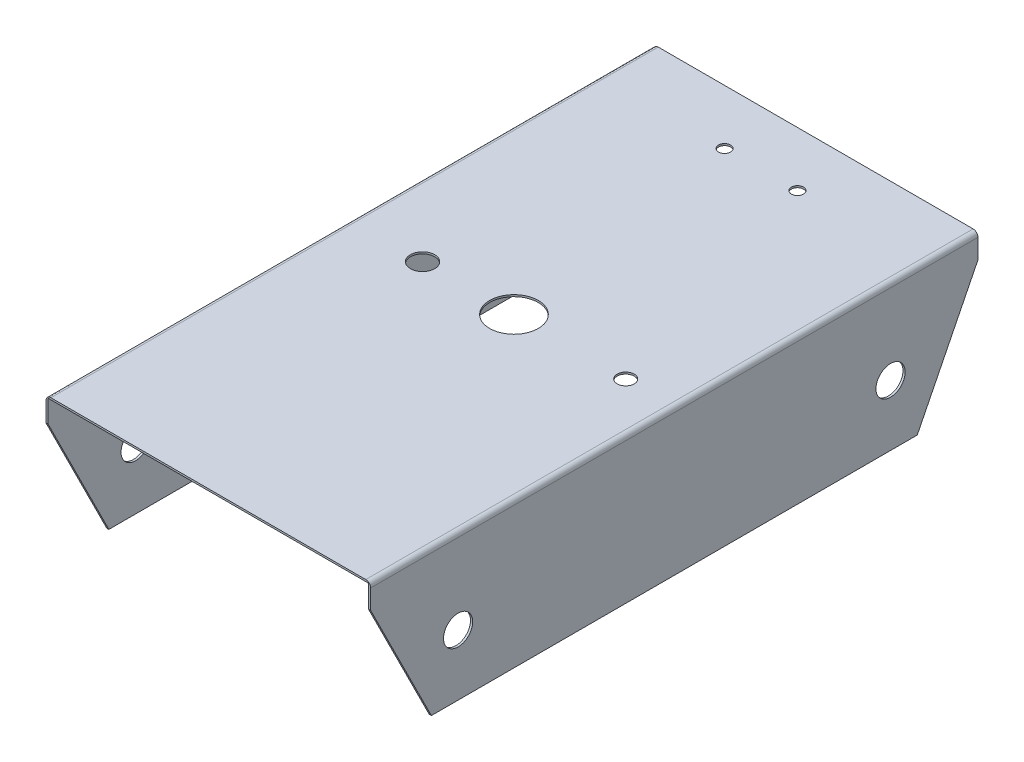
SolidWorks part; units mm, degrees
material "AISI 1020"
ref_plane "Front Plane" through (0, 0, 0) normal (0, 0, 1) x (1, 0, 0)
ref_plane "Top Plane" through (0, 0, 0) normal (0, 1, 0) x (1, 0, 0)
ref_plane "Right Plane" through (0, 0, 0) normal (1, 0, 0) x (0, 0, -1)
sketch "Sketch1" plane through (0, 0, 0) normal (0, 0, 1) x (1, 0, 0)
  line L0 (-66.81, -60) -> (-66.81, 0)
  line L1 (-66.81, 0) -> (66.81, 0)
  line L2 (66.81, 0) -> (66.81, -60)
  line L3 (66.81, -60) -> (65.93, -60)
  line L4 (65.93, -60) -> (65.93, -0.75)
  line L5 (65.93, -0.75) -> (-65.93, -0.75)
  line L6 (-65.93, -0.75) -> (-65.93, -60)
  line L7 (-65.93, -60) -> (-66.81, -60)
  point P3 (0, 0)
  dimension "D1" = 60
  dimension "D2" = 133.62
  dimension "D3" = 0.88
  dimension "D4" = 0.88
  dimension "D5" = 59.25
extrude "Boss-Extrude1" add sketch "Sketch1" along normal blind 250
sketch "Sketch2" plane through (66.81, 0, 0) normal (1, 0, 0) x (0, 0, -1)
  line L0 (-250, 0) -> (-250, -10)
  line L1 (-250, -60) -> (-250, 0) construction
  line L2 (-250, -10) -> (-225, -60)
  line L3 (-250, -60) -> (0, -60) construction
  line L4 (0, 0) -> (0, -10)
  line L5 (0, -60) -> (0, 0) construction
  line L6 (0, -10) -> (-25, -60)
  line L7 (-225, -60) -> (-250, -60)
  line L8 (-250, -60) -> (-250, -10)
  line L9 (-25, -60) -> (0, -60)
  line L10 (0, -60) -> (0, -10)
  line M3 (0, -60) -> (0, 0)
  line M5 (-250, 0) -> (-250, -60)
  line M6 (-250, -60) -> (0, -60)
  dimension "D1" = 25
  dimension "D2" = 25
  dimension "D3" = 10
  dimension "D4" = 10
extrude "Cut-Extrude1" cut sketch "Sketch2" against normal blind 250 contours L2 M5 M6 | L6 M3 M6
sketch "Sketch3" plane through (66.81, 0, 0) normal (1, 0, 0) x (0, 0, -1)
  line L0 (-250, -10) -> (-250, -60) construction
  line L1 (-250, -35) -> (-214, -35) construction
  line L2 (-214, -35) -> (-36, -35) construction
  line L4 (-225, -60) -> (-25, -60) construction
  line L6 (0, -10) -> (0, 0) construction
  circle A0 centre (-214, -35) radius 6
  circle A1 centre (-36, -35) radius 6
  point P9 (-250, -35)
  dimension "D1" = 12
  dimension "D2" = 12
  dimension "D3" = 36
  dimension "D4" = 178
  dimension "D5" = 36
  dimension "D6" = 25
extrude "Cut-Extrude2" cut sketch "Sketch3" against normal through all both and the other way through all
fillet "Fillet1" radius 2 2 edges at (-66.81, 0, 125) (66.81, 0, 125)
sketch "Sketch5" plane through (0, 0, 0) normal (0, 1, 0) x (1, 0, 0)
  line L0 (66.81, 0) -> (66.81, -250) construction
  line L1 (64.81, -250) -> (-64.81, -250) construction
  line L2 (-66.81, -250) -> (-66.81, 0) construction
  circle A0 centre (0.81, -125) radius 10
  dimension "D1" = 20
  dimension "D2" = 66
  dimension "D3" = 125
  dimension "D4" = 67.62
extrude "Cut-Extrude3" cut sketch "Sketch5" against normal blind 10
sketch "Sketch6" plane through (-65.93, 0, 0) normal (1, 0, 0) x (0, 0, -1)
  line L0 (-250, -0.75) -> (0, -0.75) construction
  line L1 (-178, -0.75) -> (-88, -0.75)
  line L2 (-178, -0.75) -> (-178, -60.75)
  line L3 (-178, -60.75) -> (-88, -60.75)
  line L4 (-88, -0.75) -> (-88, -60.75)
  line L7 (-250, -10) -> (-250, -0.75) construction
  line L8 (0, -10) -> (0, -0.75) construction
  circle A0 centre (-173, -55.7) radius 2.5
  circle A1 centre (-93, -55.7) radius 2.5
  circle A2 centre (-93, -5.7) radius 2.5
  circle A3 centre (-173, -5.7) radius 2.5
  point P4 (-133, 19.479)
  point P9 (-250, -5.375)
  dimension "D4" = 5
  dimension "D5" = 5
  dimension "D6" = 5
  dimension "D7" = 5
  dimension "D1" = 72
  dimension "D2" = 88
  dimension "D3" = 60
  dimension "D8" = 5.05
  dimension "D9" = 5
  dimension "D10" = 5
  dimension "D11" = 4.95
  dimension "D12" = 4.95
  dimension "D13" = 5
  dimension "D14" = 5
  dimension "D15" = 5.05
extrude "Cut-Extrude4" cut sketch "Sketch6" against normal blind 10 contours A0 | A1 | A3 | A2
sketch "Sketch7" plane through (0, 0, 0) normal (0, 1, 0) x (1, 0, 0)
  line L0 (66.81, 0) -> (66.81, -250) construction
  line L1 (64.81, 0) -> (-64.81, 0) construction
  line L3 (-66.81, -250) -> (-66.81, 0) construction
  circle A0 centre (46.81, -125) radius 3.5
  circle A1 centre (-36.81, -125) radius 5
  dimension "D3" = 7
  dimension "D4" = 10
  dimension "D1" = 20
  dimension "D2" = 125
  dimension "D5" = 30
  dimension "D6" = 125
extrude "Cut-Extrude5" cut sketch "Sketch7" against normal blind 10
sketch "Sketch9" plane through (0, 0, 0) normal (0, 1, 0) x (1, 0, 0)
  circle A0 centre (-15, -22.5) radius 2.5
  circle A3 centre (15, -22.5) radius 2.5
  dimension "D3" = 15
  dimension "D1" = 5
  dimension "D2" = 5
  dimension "D4" = 15
  dimension "D5" = 22.5
  dimension "D6" = 22.5
extrude "Cut-Extrude8" cut sketch "Sketch9" against normal blind 14 contours A0 | A3
